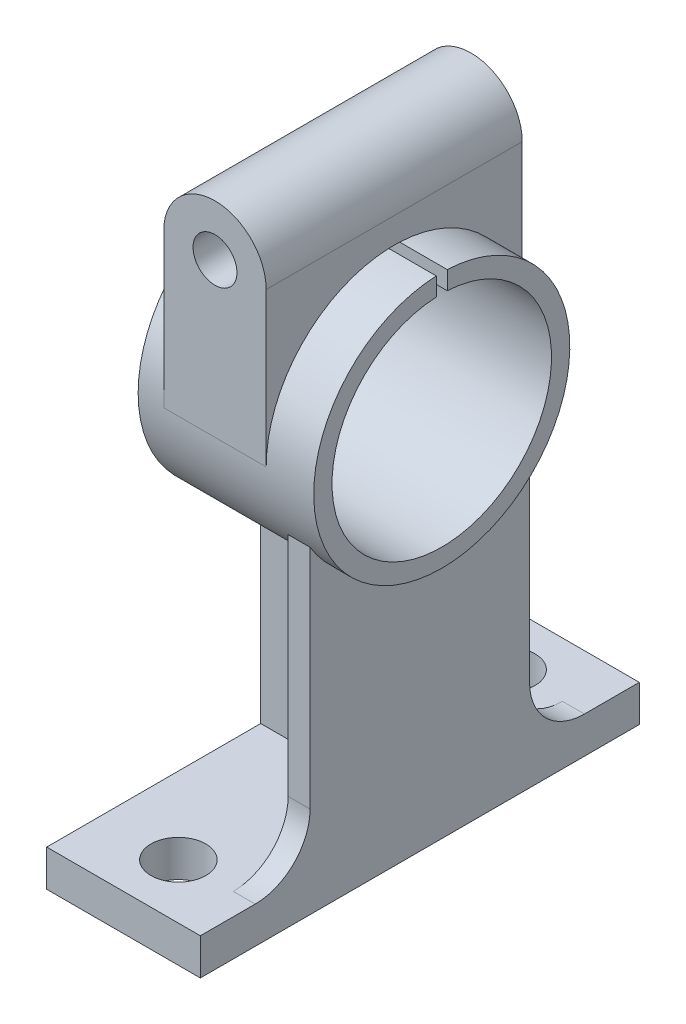
SolidWorks part; units mm, degrees
ref_plane "Front Plane" through (0, 0, 0) normal (0, 0, 1) x (1, 0, 0)
ref_plane "Top Plane" through (0, 0, 0) normal (0, 1, 0) x (1, 0, 0)
ref_plane "Right Plane" through (0, 0, 0) normal (1, 0, 0) x (0, 0, -1)
sketch "Sketch1" plane through (0, 0, 0) normal (0, 1, 0) x (1, 0, 0)
  line L1 (0, 0) -> (42, 0)
  line L2 (0, 0) -> (0, 120)
  line L3 (0, 120) -> (42, 120)
  line L4 (42, 0) -> (42, 120)
  circle A0 centre (21, 15) radius 7.5
  circle A1 centre (21, 105) radius 7.5
  dimension "D3" = 15
  dimension "D4" = 15
  dimension "D1" = 120
  dimension "D2" = 42
  dimension "D5" = 90
  dimension "D6" = 21
extrude "Boss-Extrude1" add sketch "Sketch1" along normal blind 10
sketch "Sketch2" plane through (42, 0, 0) normal (1, 0, 0) x (0, 0, -1)
  line L0 (0, 0) -> (120, 0) construction
  line L2 (90, 25) -> (90, 86.9722)
  line L3 (30, 25) -> (30, 86.9722)
  line L9 (15, 10) -> (105, 10)
  arc A0 (30, 86.9722) -> (90, 86.9722) centre (60, 105) ccw
  arc A1 (90, 25) -> (105, 10) centre (105, 25) ccw
  arc A2 (30, 25) -> (15, 10) centre (15, 25) cw
  point P0 (0, 0)
  point P4 (60, 70)
  point P5 (60, 10)
  point P20 (90, 10)
  dimension "D1" = 60
  dimension "D3" = 15
  dimension "D2" = 35
  dimension "D4" = 60
  dimension "D5" = 10
  dimension "D6" = 70
extrude "Boss-Extrude2" add sketch "Sketch2" against normal blind 6
sketch "Sketch3" plane through (42, 0, 0) normal (1, 0, 0) x (0, 0, -1)
  line L2 (61.5, 134.9625) -> (61.5, 139.9678)
  line L3 (58.5, 134.9625) -> (58.5, 139.9678)
  arc A0 (58.5, 139.9678) -> (61.5, 139.9678) centre (60, 105) ccw
  arc A1 (58.5, 134.9625) -> (61.5, 134.9625) centre (60, 105) ccw
  dimension "D1" = 60
  dimension "D2" = 70
  dimension "D3" = 3
extrude "Boss-Extrude3" add sketch "Sketch3" along normal blind 6 and the other way blind 42
sketch "Sketch4" plane through (36, 0, 0) normal (-1, 0, 0) x (0, 0, 1)
  line L0 (-61.5, 10) -> (-58.5, 10)
  line L2 (-61.5, 70.0322) -> (-61.5, 10)
  line L3 (-58.5, 70.0322) -> (-58.5, 10)
  arc A0 (-61.5, 70.0322) -> (-58.5, 70.0322) centre (-60, 105) ccw
  dimension "D3" = 35
  dimension "D1" = 3
  dimension "D2" = 60.0322
extrude "Boss-Extrude4" add sketch "Sketch4" along normal blind 36
sketch "Sketch5" plane through (0, 0, 0) normal (0, 0, 1) x (1, 0, 0)
  line L1 (7, 105) -> (35, 105)
  line L2 (7, 147) -> (7, 105)
  line L3 (35, 147) -> (35, 105)
  line L5 (0, 10) -> (36, 10) construction
  line L6 (0, 139.9678) -> (0, 70.0322) construction
  line L7 (0, 10) -> (0, 0) construction
  circle A0 centre (21, 147) radius 6
  arc A1 (35, 147) -> (7, 147) centre (21, 147) ccw
  point P2 (18, 10)
  dimension "D1" = 28
  dimension "D3" = 12
  dimension "D2" = 137
  dimension "D4" = 21
  dimension "D5" = 105
extrude "Boss-Extrude7" add sketch "Sketch5" against normal blind 70 from offset 25 offset against normal yes
sketch "Sketch6" plane through (48, 0, 0) normal (1, 0, 0) x (0, 0, -1)
  line L0 (90, 105) -> (30, 105) construction
  line L1 (58.5, 139.9678) -> (58.5, 134.9625)
  line L2 (61.5, 139.9678) -> (61.5, 134.9625)
  arc A0 (58.5, 134.9625) -> (61.5, 134.9625) centre (60, 105) ccw
  arc A1 (61.5, 139.9678) -> (58.5, 139.9678) centre (60, 105) ccw
extrude "Cut-Extrude1" cut sketch "Sketch6" against normal blind 70
